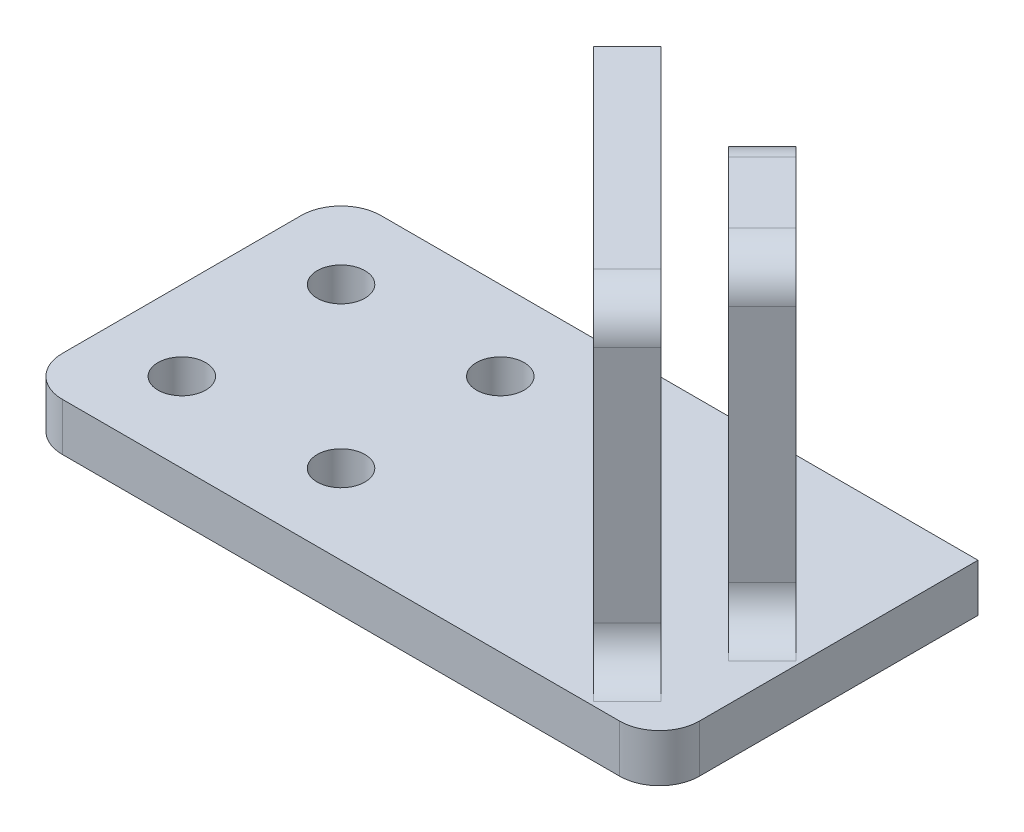
SolidWorks part; units mm, degrees
ref_plane "Front Plane" through (0, 0, 0) normal (0, 0, 1) x (1, 0, 0)
ref_plane "Top Plane" through (0, 0, 0) normal (0, 1, 0) x (1, 0, 0)
ref_plane "Right Plane" through (0, 0, 0) normal (1, 0, 0) x (0, 0, -1)
sketch "Sketch2" plane through (0, 0, 0) normal (0, 1, 0) x (1, 0, 0)
  line L1 (0, 0) -> (40, 0)
  line L2 (0, 0) -> (0, 20)
  line L3 (0, 20) -> (40, 20)
  line L4 (40, 0) -> (40, 20)
  circle A0 centre (5, 5) radius 1.5
  circle A1 centre (15, 5) radius 1.5
  circle A2 centre (15, 15) radius 1.5
  circle A3 centre (5, 15) radius 1.5
  dimension "D3" = 5
  dimension "D4" = 5
  dimension "D5" = 3
  dimension "D8" = 10
  dimension "D9" = 10
  dimension "D10" = 5
  dimension "D1" = 40
  dimension "D2" = 20
  dimension "D6" = 2
  dimension "D7" = 2
extrude "Boss-Extrude1" add sketch "Sketch2" along normal blind 3
sketch "Sketch3" plane through (0, 3, 0) normal (0, 1, 0) x (1, 0, 0)
  line L0 (22.0972, 18) -> (35.9758, 4.1213)
  line L1 (35.9758, 4.1213) -> (33.8545, 2)
  line L2 (33.8545, 2) -> (19.9758, 15.8787)
  line L3 (40, 20) -> (0, 20) construction
  line L5 (35.8787, 8.4611) -> (28.4611, 15.8787)
  line L6 (28.4611, 15.8787) -> (30.5824, 18)
  line L7 (30.5824, 18) -> (38, 10.5824)
  line L8 (38, 10.5824) -> (35.8787, 8.4611)
  line L13 (40, 0) -> (40, 20) construction
  line L14 (0, 0) -> (40, 0) construction
  line L15 (22.0972, 18) -> (19.9758, 15.8787)
  dimension "D1" = 2
  dimension "D2" = 3
  dimension "D3" = 3
  dimension "D4" = 2
  dimension "D5" = 2
  dimension "D6" = 45
  dimension "D7" = 2
  dimension "D8" = 10.49
  dimension "D9" = 3
extrude "Boss-Extrude2" add sketch "Sketch3" along normal blind 20
sketch "Sketch4" plane through (24.2912, 0, -24.2912) normal (0.7071, 0, -0.7071) x (-0.7071, 0, -0.7071)
  line L0 (-8.8971, 23) -> (-8.8971, 3) construction
  line L2 (-8.8971, 3) -> (-19.3871, 3) construction
  circle A0 centre (-13.8971, 18) radius 1.5
  circle A1 centre (-13.8971, 13) radius 1.5
  circle A2 centre (-13.8971, 8) radius 1.5
  dimension "D1" = 5
  dimension "D2" = 5
  dimension "D4" = 3
  dimension "D3" = 3
extrude "Cut-Extrude1" cut sketch "Sketch4" against normal blind 20
fillet "Fillet2" radius 2.5 9 edges at (0, 1.5, -20) (40, 1.5, 0) (34.9152, 23, -3.0607) (29.5218, 23, -16.9393) (36.9393, 23, -9.5218) (36.9393, 3, -9.5218) (29.5218, 3, -16.9393) (34.9152, 3, -3.0607) (0, 1.5, 0)
